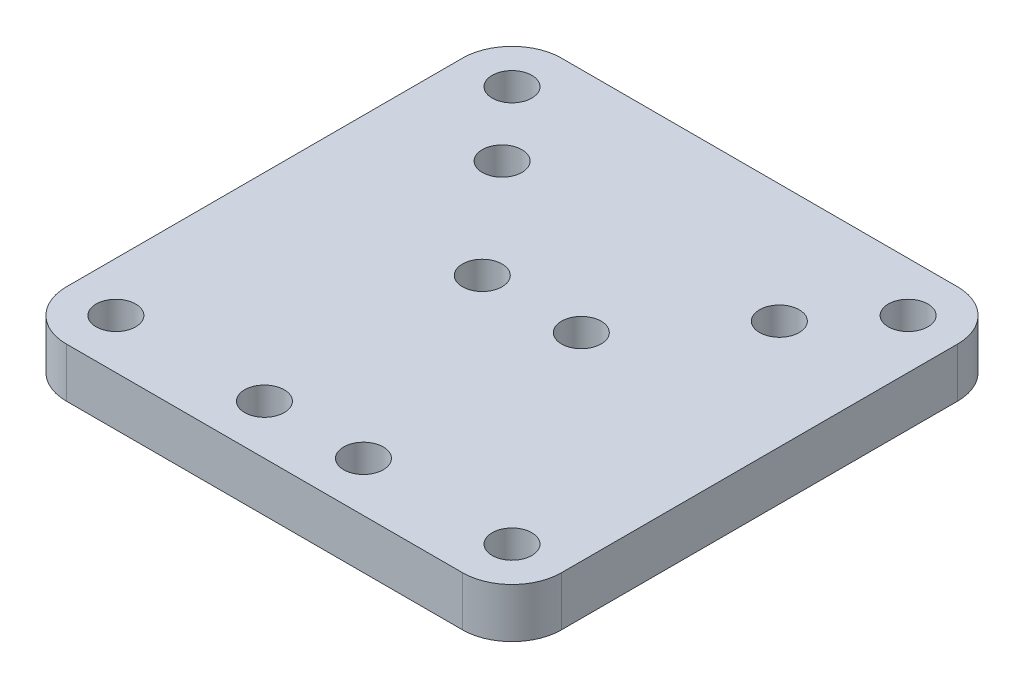
SolidWorks part; units mm, degrees
ref_plane "Plan de face" through (0, 0, 0) normal (0, 0, 1) x (1, 0, 0)
ref_plane "Plan de dessus" through (0, 0, 0) normal (0, 1, 0) x (1, 0, 0)
ref_plane "Plan de droite" through (0, 0, 0) normal (1, 0, 0) x (0, 0, -1)
sketch "Esquisse1" plane through (0, 0, 0) normal (0, 1, 0) x (1, 0, 0)
  line L0 (-62.6092, 0) -> (63.2078, 0) construction
  line L1 (25, -25) -> (-25, -25)
  line L2 (25, -25) -> (25, 25)
  line L3 (25, 25) -> (-25, 25)
  line L4 (-25, -25) -> (-25, 25)
  line L5 (25, -25) -> (-25, 25) construction
  line L6 (25, 25) -> (-25, -25) construction
  line L7 (-5, -20) -> (5, -20) construction
  line L8 (0, 21.3033) -> (0, -22.1041) construction
  line L11 (-5, 20) -> (5, 20) construction
  circle A0 centre (-5, -20) radius 2
  circle A1 centre (5, -20) radius 2
  circle A8 centre (-5, 2) radius 2
  circle A9 centre (5, 2) radius 2
  point P0 (0, 0)
  point P13 (0, 20)
  point P19 (0, 0)
  point P20 (0, 0)
  point P21 (0, 0)
  dimension "D1" = 50
  dimension "D3" = 4
  dimension "D4" = 4
  dimension "D7" = 4
  dimension "D8" = 4
  dimension "D2" = 50
  dimension "D5" = 10
  dimension "D6" = 5
  dimension "D9" = 22
extrude "Boss.-Extru.1" add sketch "Esquisse1" along normal blind 5
fillet "Congé1" radius 5 4 edges at (25, 2.5, 25) (25, 2.5, -25) (-25, 2.5, 25) (-25, 2.5, -25)
sketch "Esquisse2" plane through (0, 5, 0) normal (0, 1, 0) x (1, 0, 0)
  line L1 (-25, 0) -> (26.9694, 0) construction
  line L2 (-25, 20) -> (-25, -20) construction
  line L3 (20, 25) -> (-20, 25) construction
  line L4 (25, -20) -> (25, 20) construction
  circle A0 centre (-20, 20) radius 2
  circle A1 centre (-20, -20) radius 2
  circle A2 centre (20, -20) radius 2
  circle A3 centre (20, 20) radius 2
  circle A4 centre (-14, 13) radius 2
  circle A5 centre (14, 13) radius 2
  dimension "D1" = 4
  dimension "D2" = 4
  dimension "D3" = 4
  dimension "D4" = 4
  dimension "D5" = 4
  dimension "D6" = 4
  dimension "D7" = 12
  dimension "D8" = 11
  dimension "D9" = 12
  dimension "D10" = 11
extrude "Enlèv. mat.-Extru.1" cut sketch "Esquisse2" against normal blind 10
